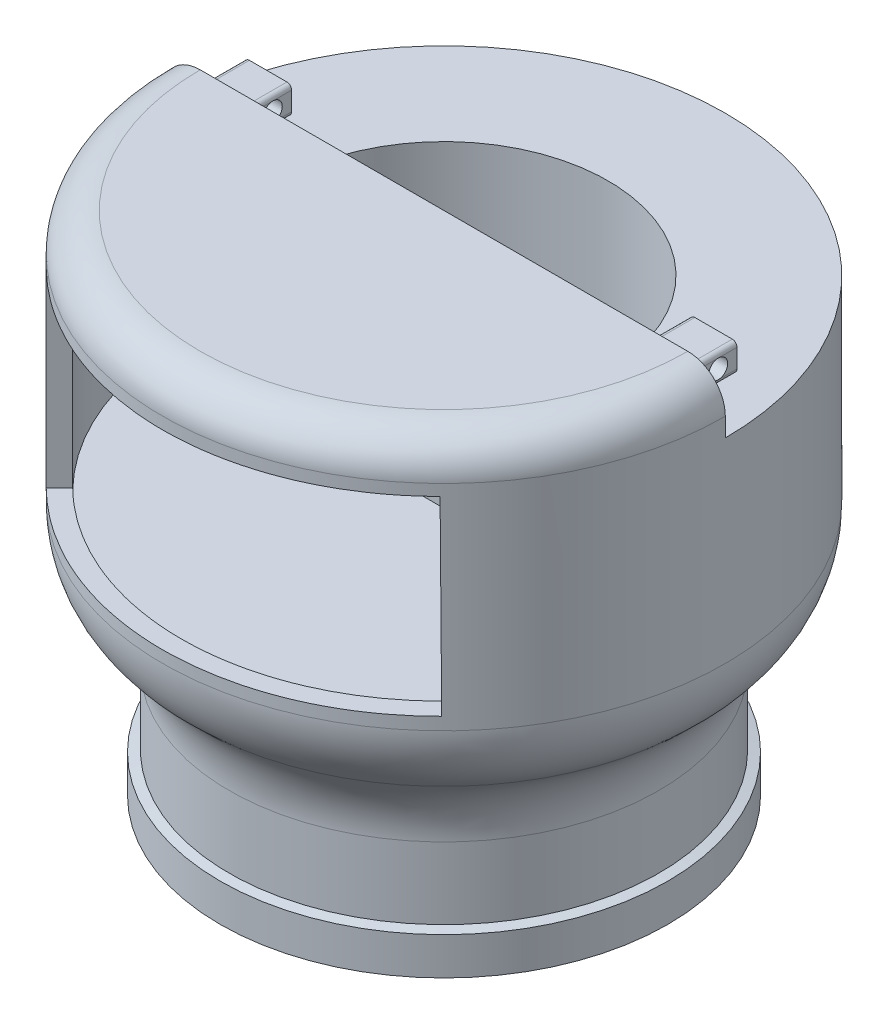
SolidWorks part; units mm, degrees
ref_plane "Front Plane" through (0, 0, 0) normal (0, 0, 1) x (1, 0, 0)
ref_plane "Top Plane" through (0, 0, 0) normal (0, 1, 0) x (1, 0, 0)
ref_plane "Right Plane" through (0, 0, 0) normal (1, 0, 0) x (0, 0, -1)
sketch "Sketch1" plane through (0, 0, 0) normal (0, 0, 1) x (1, 0, 0)
  line L0 (0, 0) -> (0, 57.8936) construction
  line L1 (20.9, 0) -> (23.8716, 0)
  line L2 (23.8716, 0) -> (23.8716, 4)
  line L3 (23.8716, 4) -> (22.9, 4.2367)
  line L4 (22.9, 4.2367) -> (22.9, 11.8746)
  line L6 (20.9, 0) -> (20.9, 14)
  line L12 (19.9, 15) -> (0, 15)
  line L17 (26.4721, 19.535) -> (26.4279, 19.4979)
  line L18 (30, 27.1583) -> (30, 50)
  line L20 (26, 54) -> (0, 54)
  line L22 (0, 15) -> (0, 54)
  arc A1 (30, 50) -> (26, 54) centre (26, 50) ccw
  arc A2 (26.4721, 19.535) -> (22.9, 11.8746) centre (32.9, 11.8746) ccw
  arc A3 (26.4279, 19.4979) -> (30, 27.1583) centre (20, 27.1583) ccw
  arc A6 (20.9, 14) -> (19.9, 15) centre (19.9, 14) ccw
  point P11 (22.9, 54)
  point P28 (28.5604, 23.4279)
  point P31 (20.9, 17)
  dimension "D9" = 4
  dimension "D4" = 30
  dimension "D16" = 10
  dimension "D19" = 1
  dimension "D2" = 4
  dimension "D3" = 1
  dimension "D6" = 2
  dimension "D7" = 2.9716
  dimension "D11" = 15
  dimension "D15" = 10
revolve "Revolve1" add sketch "Sketch1" angle 360 about L0
ref_plane "Plane1" through (0, 4, 0) normal (0, 1, 0) x (1, 0, 0)
sketch "Sketch3" plane through (0, 0, 0) normal (0, 0, 1) x (1, 0, 0)
  point P0 (1.2404, 19.1989)
ref_point "Point1"
ref_plane "Plane2" through (0, 0, 22.9) normal (0, 0, 1) x (1, 0, 0)
ref_plane "Plane3" through (0, 0, 30) normal (0, 0, 1) x (1, 0, 0)
ref_plane "Plane4" through (0, 50, 0) normal (0, -1, 0) x (-1, 0, 0)
sketch "Sketch9" plane through (0, 50, 0) normal (0, -1, 0) x (-1, 0, 0)
  line L0 (-30, 0) -> (30, 0)
  arc A0 (30, 0) -> (-30, 0) centre (0, 0) ccw
  circle A3 centre (0, 0) radius 26 construction
  dimension "D1" = 60
  dimension "D3" = 30
  dimension "D4" = 0
ref_plane "Plane5" through (0, 19.535, 0) normal (0, -1, 0) x (-1, 0, 0)
sketch "Sketch11" plane through (0, 19.535, 0) normal (0, -1, 0) x (-1, 0, 0)
  line L0 (-17.5, 0) -> (17.5, 0)
  arc A1 (-17.5, 0) -> (17.5, 0) centre (0, 0) cw
  dimension "D1" = 35
extrude "Cut-Extrude3" cut sketch "Sketch11" against normal blind 40 and the other way blind 25
ref_plane "Plane6" through (0, 0, -30) normal (0, 0, -1) x (-1, 0, 0)
extrude "Cut-Extrude5" cut sketch "Sketch9" against normal blind 5 and the other way blind 2
sketch "Sketch13" plane through (0, 0, 0) normal (0, 0, -1) x (-1, 0, 0)
  line L0 (-26, 54) -> (26, 54) construction
  line L1 (21.75, 52.5) -> (25.75, 52.5)
  line L2 (21.25, 52) -> (21.25, 50)
  line L3 (21.75, 49.5) -> (25.75, 49.5)
  line L4 (26.25, 52) -> (26.25, 50)
  line L5 (21.25, 52.5) -> (26.25, 49.5) construction
  line L6 (21.25, 49.5) -> (26.25, 52.5) construction
  line L7 (-30, 48) -> (-30, 50) construction
  line L9 (-25.75, 52.5) -> (-21.75, 52.5)
  line L10 (-26.25, 52) -> (-26.25, 50)
  line L11 (-25.75, 49.5) -> (-21.75, 49.5)
  line L12 (-21.25, 52) -> (-21.25, 50)
  line L13 (-26.25, 52.5) -> (-21.25, 49.5) construction
  line L14 (-26.25, 49.5) -> (-21.25, 52.5) construction
  arc A0 (25.75, 49.5) -> (26.25, 50) centre (25.75, 50) ccw
  arc A1 (26.25, 52) -> (25.75, 52.5) centre (25.75, 52) ccw
  arc A2 (21.75, 52.5) -> (21.25, 52) centre (21.75, 52) ccw
  arc A3 (21.25, 50) -> (21.75, 49.5) centre (21.75, 50) ccw
  arc A4 (-25.75, 52.5) -> (-26.25, 52) centre (-25.75, 52) ccw
  arc A5 (-26.25, 50) -> (-25.75, 49.5) centre (-25.75, 50) ccw
  arc A6 (-21.75, 49.5) -> (-21.25, 50) centre (-21.75, 50) ccw
  arc A7 (-21.75, 52.5) -> (-21.25, 52) centre (-21.75, 52) cw
  point P0 (23.75, 51)
  point P7 (-23.75, 51)
  dimension "D9" = 0.5
  dimension "D1" = 3
  dimension "D2" = 3
  dimension "D3" = 3
  dimension "D4" = 5
  dimension "D5" = 5
  dimension "D6" = 3
  dimension "D7" = 6.25
  dimension "D8" = 6.25
extrude "Boss-Extrude2" add sketch "Sketch13" along normal blind 5
sketch "Sketch14" plane through (21.25, 0, 0) normal (-1, 0, 0) x (0, 0, 1)
  line L0 (-5, 50) -> (0, 50) construction
  line L1 (-5, 50) -> (-5, 52) construction
  circle A0 centre (-3, 51) radius 1
  dimension "D1" = 2
  dimension "D2" = 1
  dimension "D3" = 2
sketch "Sketch15" plane through (-21.25, 0, 0) normal (1, 0, 0) x (0, 0, -1)
  line L0 (5, 52) -> (0, 52) construction
  line L1 (5, 52) -> (5, 50) construction
  circle A0 centre (3, 51) radius 1
  dimension "D1" = 2
  dimension "D2" = 1
  dimension "D3" = 2
sketch "Sketch16" plane through (0, 50, 0) normal (0, -1, 0) x (-1, 0, 0)
  line L0 (27.9598, -1.5) -> (-27.9598, -1.5)
  line L3 (17.5, 0) -> (30, 0) construction
  arc A0 (-27.9598, -1.5) -> (27.9598, -1.5) centre (0, 0) ccw
  arc A1 (-30, 0) -> (30, 0) centre (0, 0) ccw construction
  dimension "D1" = 2
  dimension "D2" = 1.5
extrude "Cut-Extrude6" cut sketch "Sketch16" along normal blind 22
sketch "Sketch17" plane through (0, 0, 0) normal (1, 0, 0) x (0, 0, -1)
  line L0 (-25.3839, 28.4283) -> (-32.3839, 28.4283)
  line L1 (-32.3839, 28.4283) -> (-32.3839, 48.7323)
  line L2 (-32.3839, 48.7323) -> (-25.3839, 48.7323)
  line L3 (-25.3839, 48.7323) -> (-25.3839, 28.4283)
  line L5 (30, 27.1583) -> (-30, 27.1583) construction
  line L10 (0, 0) -> (-0.5985, 69.9374) construction
  line L11 (-23.8716, 0) -> (23.8716, 0) construction
  dimension "D1" = 7
  dimension "D2" = 1.27
revolve "Cut-Revolve1" cut sketch "Sketch17" angle 45 about L10 other way angle 45
extrude "Cut-Extrude7" cut sketch "Sketch14" against normal blind 10 contours A0
extrude "Cut-Extrude8" cut sketch "Sketch15" against normal blind 10 contours A0
